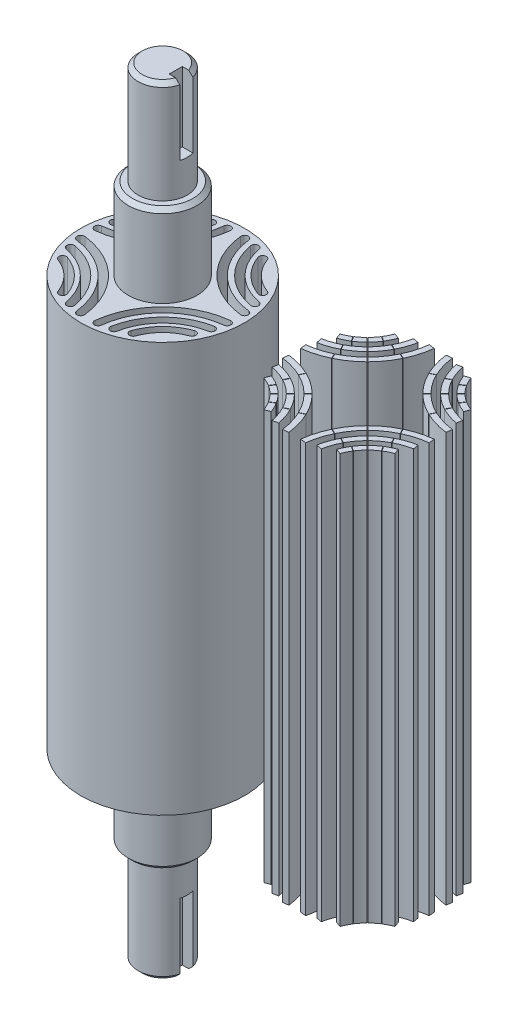
SolidWorks part; units mm, degrees
ref_plane "前视基准面" through (0, 0, 0) normal (0, 0, 1) x (1, 0, 0)
ref_plane "上视基准面" through (0, 0, 0) normal (0, 1, 0) x (1, 0, 0)
ref_plane "右视基准面" through (0, 0, 0) normal (1, 0, 0) x (0, 0, -1)
sketch "草图1" plane through (0, 0, 0) normal (0, 1, 0) x (1, 0, 0)
  circle A0 centre (0, 0) radius 20
extrude "凸台-拉伸1" add sketch "草图1" along normal blind 50
sketch "草图3" plane through (0, 50, 0) normal (0, 1, 0) x (1, 0, 0)
  circle A0 centre (0, 0) radius 8.4
extrude "凸台-拉伸2" add sketch "草图3" along normal blind 20
sketch "草图4" plane through (0, 70, 0) normal (0, 1, 0) x (1, 0, 0)
  circle A0 centre (0, 0) radius 6
extrude "凸台-拉伸3" add sketch "草图4" along normal blind 25
chamfer "倒角1" distance 1 angle 45 1 edges at (0, 70, 8.4)
chamfer "倒角2" distance 1 angle 45 1 edges at (0, 95, 6)
ref_plane "基准面1" through (10, 0, 0) normal (1, 0, 0) x (0, 0, -1)
sketch "草图5" plane through (10, 0, 0) normal (1, 0, 0) x (0, 0, -1)
  line L0 (-6, 94) -> (6, 94) construction
  line L1 (-1.6, 110) -> (1.6, 110)
  line L2 (-1.6, 110) -> (-1.6, 78)
  line L3 (-1.6, 78) -> (1.6, 78)
  line L4 (1.6, 110) -> (1.6, 78)
  line L5 (-1.6, 110) -> (1.6, 78) construction
  line L6 (-1.6, 78) -> (1.6, 110) construction
  point P0 (0, 94)
  dimension "D1" = 3.2
  dimension "D2" = 32
extrude "切除-拉伸1" cut sketch "草图5" against normal blind 6.8
sketch "草图6" plane through (0, 0, 0) normal (0, -1, 0) x (1, 0, 0)
  line L0 (0, 0) -> (0, 20) construction
  line L1 (0, 0) -> (20, 0) construction
  line L2 (0, 0) -> (19.8955, 19.8955) construction
  circle A0 centre (0, 0) radius 8.4 construction
  circle A1 centre (0, 0) radius 20 construction
  circle A2 centre (0, 0) radius 18 construction
  circle A3 centre (19.8955, 19.8955) radius 17.8842 construction
  circle A4 centre (19.8955, 19.8955) radius 15 construction
  circle A5 centre (19.8955, 19.8955) radius 12 construction
  arc A6 (2.126, 17.874) -> (17.874, 2.126) centre (19.8955, 19.8955) ccw construction
  arc A7 (1.2318, 17.7723) -> (17.7723, 1.2318) centre (19.8955, 19.8955) ccw
  arc A8 (3.0202, 17.9757) -> (17.9757, 3.0202) centre (19.8955, 19.8955) ccw
  arc A9 (3.0202, 17.9757) -> (1.2318, 17.7723) centre (2.126, 17.874) ccw
  arc A10 (17.7723, 1.2318) -> (17.9757, 3.0202) centre (17.874, 2.126) ccw
  arc A11 (5.3183, 17.1964) -> (17.1964, 5.3183) centre (19.8955, 19.8955) ccw construction
  arc A12 (4.4334, 17.0325) -> (17.0325, 4.4334) centre (19.8955, 19.8955) ccw
  arc A13 (6.2033, 17.3602) -> (17.3602, 6.2033) centre (19.8955, 19.8955) ccw
  arc A14 (6.2033, 17.3602) -> (4.4334, 17.0325) centre (5.3183, 17.1964) ccw
  arc A15 (17.0325, 4.4334) -> (17.3602, 6.2033) centre (17.1964, 5.3183) ccw
  arc A16 (8.6143, 15.8049) -> (15.8049, 8.6143) centre (19.8955, 19.8955) ccw construction
  arc A17 (7.7682, 15.4981) -> (15.4981, 7.7682) centre (19.8955, 19.8955) ccw
  arc A18 (9.4604, 16.1117) -> (16.1117, 9.4604) centre (19.8955, 19.8955) ccw
  arc A19 (9.4604, 16.1117) -> (7.7682, 15.4981) centre (8.6143, 15.8049) ccw
  arc A20 (15.4981, 7.7682) -> (16.1117, 9.4604) centre (15.8049, 8.6143) ccw
  arc A21 (17.874, -2.126) -> (2.126, -17.874) centre (19.8955, -19.8955) ccw construction
  arc A22 (17.7723, -1.2318) -> (1.2318, -17.7723) centre (19.8955, -19.8955) ccw
  arc A23 (17.9757, -3.0202) -> (3.0202, -17.9757) centre (19.8955, -19.8955) ccw
  arc A24 (17.9757, -3.0202) -> (17.7723, -1.2318) centre (17.874, -2.126) ccw
  arc A25 (1.2318, -17.7723) -> (3.0202, -17.9757) centre (2.126, -17.874) ccw
  arc A26 (17.1964, -5.3183) -> (5.3183, -17.1964) centre (19.8955, -19.8955) ccw construction
  arc A27 (17.0325, -4.4334) -> (4.4334, -17.0325) centre (19.8955, -19.8955) ccw
  arc A28 (17.3602, -6.2033) -> (6.2033, -17.3602) centre (19.8955, -19.8955) ccw
  arc A29 (17.3602, -6.2033) -> (17.0325, -4.4334) centre (17.1964, -5.3183) ccw
  arc A30 (4.4334, -17.0325) -> (6.2033, -17.3602) centre (5.3183, -17.1964) ccw
  arc A31 (15.8049, -8.6143) -> (8.6143, -15.8049) centre (19.8955, -19.8955) ccw construction
  arc A32 (15.4981, -7.7682) -> (7.7682, -15.4981) centre (19.8955, -19.8955) ccw
  arc A33 (16.1117, -9.4604) -> (9.4604, -16.1117) centre (19.8955, -19.8955) ccw
  arc A34 (16.1117, -9.4604) -> (15.4981, -7.7682) centre (15.8049, -8.6143) ccw
  arc A35 (7.7682, -15.4981) -> (9.4604, -16.1117) centre (8.6143, -15.8049) ccw
  arc A36 (-2.126, -17.874) -> (-17.874, -2.126) centre (-19.8955, -19.8955) ccw construction
  arc A37 (-1.2318, -17.7723) -> (-17.7723, -1.2318) centre (-19.8955, -19.8955) ccw
  arc A38 (-3.0202, -17.9757) -> (-17.9757, -3.0202) centre (-19.8955, -19.8955) ccw
  arc A39 (-3.0202, -17.9757) -> (-1.2318, -17.7723) centre (-2.126, -17.874) ccw
  arc A40 (-17.7723, -1.2318) -> (-17.9757, -3.0202) centre (-17.874, -2.126) ccw
  arc A41 (-5.3183, -17.1964) -> (-17.1964, -5.3183) centre (-19.8955, -19.8955) ccw construction
  arc A42 (-4.4334, -17.0325) -> (-17.0325, -4.4334) centre (-19.8955, -19.8955) ccw
  arc A43 (-6.2033, -17.3602) -> (-17.3602, -6.2033) centre (-19.8955, -19.8955) ccw
  arc A44 (-6.2033, -17.3602) -> (-4.4334, -17.0325) centre (-5.3183, -17.1964) ccw
  arc A45 (-17.0325, -4.4334) -> (-17.3602, -6.2033) centre (-17.1964, -5.3183) ccw
  arc A46 (-8.6143, -15.8049) -> (-15.8049, -8.6143) centre (-19.8955, -19.8955) ccw construction
  arc A47 (-7.7682, -15.4981) -> (-15.4981, -7.7682) centre (-19.8955, -19.8955) ccw
  arc A48 (-9.4604, -16.1117) -> (-16.1117, -9.4604) centre (-19.8955, -19.8955) ccw
  arc A49 (-9.4604, -16.1117) -> (-7.7682, -15.4981) centre (-8.6143, -15.8049) ccw
  arc A50 (-15.4981, -7.7682) -> (-16.1117, -9.4604) centre (-15.8049, -8.6143) ccw
  arc A51 (-17.874, 2.126) -> (-2.126, 17.874) centre (-19.8955, 19.8955) ccw construction
  arc A52 (-17.7723, 1.2318) -> (-1.2318, 17.7723) centre (-19.8955, 19.8955) ccw
  arc A53 (-17.9757, 3.0202) -> (-3.0202, 17.9757) centre (-19.8955, 19.8955) ccw
  arc A54 (-17.9757, 3.0202) -> (-17.7723, 1.2318) centre (-17.874, 2.126) ccw
  arc A55 (-1.2318, 17.7723) -> (-3.0202, 17.9757) centre (-2.126, 17.874) ccw
  arc A56 (-17.1964, 5.3183) -> (-5.3183, 17.1964) centre (-19.8955, 19.8955) ccw construction
  arc A57 (-17.0325, 4.4334) -> (-4.4334, 17.0325) centre (-19.8955, 19.8955) ccw
  arc A58 (-17.3602, 6.2033) -> (-6.2033, 17.3602) centre (-19.8955, 19.8955) ccw
  arc A59 (-17.3602, 6.2033) -> (-17.0325, 4.4334) centre (-17.1964, 5.3183) ccw
  arc A60 (-4.4334, 17.0325) -> (-6.2033, 17.3602) centre (-5.3183, 17.1964) ccw
  arc A61 (-15.8049, 8.6143) -> (-8.6143, 15.8049) centre (-19.8955, 19.8955) ccw construction
  arc A62 (-15.4981, 7.7682) -> (-7.7682, 15.4981) centre (-19.8955, 19.8955) ccw
  arc A63 (-16.1117, 9.4604) -> (-9.4604, 16.1117) centre (-19.8955, 19.8955) ccw
  arc A64 (-16.1117, 9.4604) -> (-15.4981, 7.7682) centre (-15.8049, 8.6143) ccw
  arc A65 (-7.7682, 15.4981) -> (-9.4604, 16.1117) centre (-8.6143, 15.8049) ccw
  point P15 (7.2495, 7.2495)
  point P23 (9.4127, 9.4127)
  point P31 (11.4103, 11.4103)
  point P42 (7.2495, -7.2495)
  point P50 (9.4127, -9.4127)
  point P58 (11.4103, -11.4103)
  point P66 (-7.2495, -7.2495)
  point P74 (-9.4127, -9.4127)
  point P82 (-11.4103, -11.4103)
  point P90 (-7.2495, 7.2495)
  point P98 (-9.4127, 9.4127)
  point P106 (-11.4103, 11.4103)
  point P111 (0, 0)
  dimension "D1" = 4
extrude "切除-拉伸2" cut sketch "草图6" against normal up to next
mirror "镜向1" about plane through (0, 0, 0) normal (0, 1, 0) of bodies 110
ref_plane "基准面2" through (0, 100, 0) normal (0, 1, 0) x (1, 0, 0)
sketch "草图7" plane through (0, 100, 0) normal (0, 1, 0) x (1, 0, 0)
  line L0 (19.8955, 19.8955) -> (0, 0) construction
  line L1 (19.8955, 19.8955) -> (7.7682, 15.4981) construction
  line L2 (19.8955, 19.8955) -> (4.4334, 17.0325) construction
  line L3 (19.8955, 19.8955) -> (1.2318, 17.7723) construction
  line L4 (19.8955, 19.8955) -> (1.4795, 8.1632) construction
  line L5 (19.8955, 19.8955) -> (1.4863, 10.2099) construction
  line L6 (19.8955, 19.8955) -> (1.6731, 11.1061) construction
  line L16 (10.3383, 13.8662) -> (9.1576, 13.114)
  line L17 (10.3921, 13.7819) -> (9.2113, 13.0297)
  line L18 (9.2876, 16.0017) -> (7.9734, 15.5193)
  line L19 (11.8699, 11.9406) -> (10.8799, 10.9506)
  line L20 (9.8723, 9.943) -> (8.8824, 8.9531)
  line L21 (6.015, 17.2791) -> (4.6392, 17.0198)
  line L22 (7.3718, 13.363) -> (6.1328, 12.7111)
  line L23 (7.4184, 13.2745) -> (6.1794, 12.6226)
  line L24 (7.7091, 7.7799) -> (6.7192, 6.7899)
  line L25 (4.3961, 12.475) -> (3.1351, 11.8668)
  line L26 (4.4395, 12.3849) -> (3.1785, 11.7767)
  line L27 (2.8268, 17.9072) -> (1.4362, 17.7452)
  arc A0 (17.0325, 4.4334) -> (17.3602, 6.2033) centre (17.1964, 5.3183) ccw construction
  arc A1 (17.7723, 1.2318) -> (17.9757, 3.0202) centre (17.874, 2.126) ccw construction
  arc A2 (3.0202, 17.9757) -> (1.2318, 17.7723) centre (2.126, 17.874) ccw construction
  arc A3 (6.2033, 17.3602) -> (4.4334, 17.0325) centre (5.3183, 17.1964) ccw construction
  arc A4 (15.4981, 7.7682) -> (16.1117, 9.4604) centre (15.8049, 8.6143) ccw construction
  arc A5 (9.4604, 16.1117) -> (7.7682, 15.4981) centre (8.6143, 15.8049) ccw construction
  arc A6 (9.4604, 16.1117) -> (16.1117, 9.4604) centre (19.8955, 19.8955) ccw construction
  arc A7 (7.7682, 15.4981) -> (15.4981, 7.7682) centre (19.8955, 19.8955) ccw construction
  arc A8 (6.2033, 17.3602) -> (17.3602, 6.2033) centre (19.8955, 19.8955) ccw construction
  arc A9 (4.4334, 17.0325) -> (17.0325, 4.4334) centre (19.8955, 19.8955) ccw construction
  arc A10 (1.2318, 17.7723) -> (17.7723, 1.2318) centre (19.8955, 19.8955) ccw construction
  arc A11 (3.0202, 17.9757) -> (17.9757, 3.0202) centre (19.8955, 19.8955) ccw construction
  arc A12 (17.0325, 4.4334) -> (17.3602, 6.2033) centre (17.1964, 5.3183) ccw construction
  arc A13 (17.7723, 1.2318) -> (17.9757, 3.0202) centre (17.874, 2.126) ccw construction
  arc A14 (3.0202, 17.9757) -> (1.2318, 17.7723) centre (2.126, 17.874) ccw construction
  arc A15 (6.2033, 17.3602) -> (4.4334, 17.0325) centre (5.3183, 17.1964) ccw construction
  arc A16 (15.4981, 7.7682) -> (16.1117, 9.4604) centre (15.8049, 8.6143) ccw construction
  arc A17 (9.4604, 16.1117) -> (7.7682, 15.4981) centre (8.6143, 15.8049) ccw construction
  arc A18 (9.4604, 16.1117) -> (16.1117, 9.4604) centre (19.8955, 19.8955) ccw construction
  arc A19 (7.7682, 15.4981) -> (15.4981, 7.7682) centre (19.8955, 19.8955) ccw construction
  arc A20 (6.2033, 17.3602) -> (17.3602, 6.2033) centre (19.8955, 19.8955) ccw construction
  arc A21 (4.4334, 17.0325) -> (17.0325, 4.4334) centre (19.8955, 19.8955) ccw construction
  arc A22 (1.2318, 17.7723) -> (17.7723, 1.2318) centre (19.8955, 19.8955) ccw construction
  arc A23 (3.0202, 17.9757) -> (17.9757, 3.0202) centre (19.8955, 19.8955) ccw construction
  arc A24 (6.015, 17.2791) -> (7.3667, 13.3731) centre (19.8955, 19.8955) ccw
  arc A25 (7.4184, 13.2745) -> (9.8691, 9.9463) centre (19.8955, 19.8955) ccw
  arc A26 (10.3921, 13.7819) -> (11.868, 11.9425) centre (19.8955, 19.8955) ccw
  arc A27 (4.6392, 17.0198) -> (6.1329, 12.7112) centre (19.8955, 19.8955) ccw
  arc A28 (6.1794, 12.6226) -> (8.9177, 8.9177) centre (19.8955, 19.8955) ccw
  arc A29 (2.8268, 17.9072) -> (4.3963, 12.4747) centre (19.8955, 19.8955) ccw
  arc A30 (9.2113, 13.0297) -> (10.8747, 10.9559) centre (19.8955, 19.8955) ccw
  arc A31 (1.4362, 17.7452) -> (3.1352, 11.8668) centre (19.8955, 19.8955) ccw
  arc A32 (9.2876, 16.0017) -> (10.3393, 13.8649) centre (19.8955, 19.8955) ccw
  arc A33 (7.9734, 15.5193) -> (9.1527, 13.1219) centre (19.8955, 19.8955) ccw
  arc A34 (4.4395, 12.3849) -> (7.7011, 7.7879) centre (19.8955, 19.8955) ccw
  arc A35 (3.1785, 11.7767) -> (6.7041, 6.8051) centre (19.8955, 19.8955) ccw
  point P69 (11.9052, 11.9052)
  point P70 (11.8699, 11.9406)
  point P71 (10.8799, 10.9506)
  point P72 (10.9153, 10.9153)
  dimension "D2" = 25.069
  dimension "D3" = 34.51
  dimension "D4" = 38.51
  dimension "D5" = 12.5
  dimension "D6" = 17.25
  dimension "D7" = 19.25
ref_plane "基准面3" through (0, 50, 0) normal (0, 1, 0) x (1, 0, 0)
sketch "草图8" plane through (0, 50, 0) normal (0, 1, 0) x (1, 0, 0)
  line L0 (11.8699, 11.9406) -> (10.8799, 10.9506) construction
  line L1 (10.3921, 13.7819) -> (9.2113, 13.0297) construction
  line L2 (10.3383, 13.8662) -> (9.1576, 13.114) construction
  line L3 (9.2876, 16.0017) -> (7.9734, 15.5193) construction
  line L4 (6.015, 17.2791) -> (4.6392, 17.0198) construction
  line L5 (7.3718, 13.363) -> (6.1328, 12.7111) construction
  line L6 (7.4184, 13.2745) -> (6.1794, 12.6226) construction
  line L7 (9.8723, 9.943) -> (8.8824, 8.9531) construction
  line L8 (7.7091, 7.7799) -> (6.7192, 6.7899) construction
  line L9 (4.4395, 12.3849) -> (3.1785, 11.7767) construction
  line L10 (4.3961, 12.475) -> (3.1351, 11.8668) construction
  line L11 (2.8268, 17.9072) -> (1.4362, 17.7452) construction
  line L12 (11.8699, 11.9406) -> (10.8799, 10.9506)
  line L13 (10.3921, 13.7819) -> (9.2113, 13.0297)
  line L14 (10.3384, 13.8663) -> (9.1576, 13.114)
  line L15 (9.2876, 16.0017) -> (7.9734, 15.5193)
  line L16 (6.015, 17.2791) -> (4.6392, 17.0198)
  line L17 (7.3718, 13.363) -> (6.1328, 12.7111)
  line L18 (7.4184, 13.2745) -> (6.1794, 12.6226)
  line L19 (9.8723, 9.943) -> (8.8824, 8.9531)
  line L20 (7.7091, 7.7799) -> (6.7192, 6.7899)
  line L21 (4.4395, 12.3849) -> (3.1785, 11.7767)
  line L22 (4.3961, 12.475) -> (3.1351, 11.8668)
  line L23 (2.8268, 17.9072) -> (1.4362, 17.7452)
  line L24 (11.9406, -11.8699) -> (10.9506, -10.8799)
  line L25 (0, 0) -> (16.5885, 16.5885) construction
  line L26 (17.9072, 2.8268) -> (17.7452, 1.4362)
  line L27 (12.475, 4.3961) -> (11.8668, 3.1351)
  line L28 (12.3849, 4.4395) -> (11.7767, 3.1785)
  line L29 (7.7799, 7.7091) -> (6.7899, 6.7192)
  line L30 (9.943, 9.8723) -> (8.9531, 8.8824)
  line L31 (13.2745, 7.4184) -> (12.6226, 6.1794)
  line L32 (13.363, 7.3718) -> (12.7111, 6.1328)
  line L33 (17.2791, 6.015) -> (17.0198, 4.6392)
  line L34 (16.0017, 9.2876) -> (15.5193, 7.9734)
  line L35 (13.8663, 10.3384) -> (13.114, 9.1576)
  line L36 (13.7819, 10.3921) -> (13.0297, 9.2113)
  line L37 (11.9406, 11.8699) -> (10.9506, 10.8799)
  line L38 (13.7819, -10.3921) -> (13.0297, -9.2113)
  line L39 (13.8663, -10.3384) -> (13.114, -9.1576)
  line L40 (16.0017, -9.2876) -> (15.5193, -7.9734)
  line L41 (17.2791, -6.015) -> (17.0198, -4.6392)
  line L42 (13.363, -7.3718) -> (12.7111, -6.1328)
  line L43 (13.2745, -7.4184) -> (12.6226, -6.1794)
  line L44 (9.943, -9.8723) -> (8.9531, -8.8824)
  line L45 (7.7799, -7.7091) -> (6.7899, -6.7192)
  line L46 (12.3849, -4.4395) -> (11.7767, -3.1785)
  line L47 (12.475, -4.3961) -> (11.8668, -3.1351)
  line L48 (17.9072, -2.8268) -> (17.7452, -1.4362)
  line L49 (2.8268, -17.9072) -> (1.4362, -17.7452)
  line L50 (4.3961, -12.475) -> (3.1351, -11.8668)
  line L51 (4.4395, -12.3849) -> (3.1785, -11.7767)
  line L52 (7.7091, -7.7799) -> (6.7192, -6.7899)
  line L53 (9.8723, -9.943) -> (8.8824, -8.9531)
  line L54 (7.4184, -13.2745) -> (6.1794, -12.6226)
  line L55 (7.3718, -13.363) -> (6.1328, -12.7111)
  line L56 (6.015, -17.2791) -> (4.6392, -17.0198)
  line L57 (9.2876, -16.0017) -> (7.9734, -15.5193)
  line L58 (10.3384, -13.8663) -> (9.1576, -13.114)
  line L59 (10.3921, -13.7819) -> (9.2113, -13.0297)
  line L60 (11.8699, -11.9406) -> (10.8799, -10.9506)
  line L61 (-11.8699, -11.9406) -> (-10.8799, -10.9506)
  line L62 (-10.3921, -13.7819) -> (-9.2113, -13.0297)
  line L63 (-10.3384, -13.8663) -> (-9.1576, -13.114)
  line L64 (-9.2876, -16.0017) -> (-7.9734, -15.5193)
  line L65 (-6.015, -17.2791) -> (-4.6392, -17.0198)
  line L66 (-7.3718, -13.363) -> (-6.1328, -12.7111)
  line L67 (-7.4184, -13.2745) -> (-6.1794, -12.6226)
  line L68 (-9.8723, -9.943) -> (-8.8824, -8.9531)
  line L69 (-7.7091, -7.7799) -> (-6.7192, -6.7899)
  line L70 (-4.4395, -12.3849) -> (-3.1785, -11.7767)
  line L71 (-4.3961, -12.475) -> (-3.1351, -11.8668)
  line L72 (-2.8268, -17.9072) -> (-1.4362, -17.7452)
  line L73 (-17.9072, -2.8268) -> (-17.7452, -1.4362)
  line L74 (-12.475, -4.3961) -> (-11.8668, -3.1351)
  line L75 (-12.3849, -4.4395) -> (-11.7767, -3.1785)
  line L76 (-7.7799, -7.7091) -> (-6.7899, -6.7192)
  line L77 (-9.943, -9.8723) -> (-8.9531, -8.8824)
  line L78 (-13.2745, -7.4184) -> (-12.6226, -6.1794)
  line L79 (-13.363, -7.3718) -> (-12.7111, -6.1328)
  line L80 (-17.2791, -6.015) -> (-17.0198, -4.6392)
  line L81 (-16.0017, -9.2876) -> (-15.5193, -7.9734)
  line L82 (-13.8663, -10.3384) -> (-13.114, -9.1576)
  line L83 (-13.7819, -10.3921) -> (-13.0297, -9.2113)
  line L84 (-11.9406, -11.8699) -> (-10.9506, -10.8799)
  line L85 (-11.9406, 11.8699) -> (-10.9506, 10.8799)
  line L86 (-13.7819, 10.3921) -> (-13.0297, 9.2113)
  line L87 (-13.8663, 10.3384) -> (-13.114, 9.1576)
  line L88 (-16.0017, 9.2876) -> (-15.5193, 7.9734)
  line L89 (-17.2791, 6.015) -> (-17.0198, 4.6392)
  line L90 (-13.363, 7.3718) -> (-12.7111, 6.1328)
  line L91 (-13.2745, 7.4184) -> (-12.6226, 6.1794)
  line L92 (-9.943, 9.8723) -> (-8.9531, 8.8824)
  line L93 (-7.7799, 7.7091) -> (-6.7899, 6.7192)
  line L94 (-12.3849, 4.4395) -> (-11.7767, 3.1785)
  line L95 (-12.475, 4.3961) -> (-11.8668, 3.1351)
  line L96 (-17.9072, 2.8268) -> (-17.7452, 1.4362)
  line L97 (-2.8268, 17.9072) -> (-1.4362, 17.7452)
  line L98 (-4.3961, 12.475) -> (-3.1351, 11.8668)
  line L99 (-4.4395, 12.3849) -> (-3.1785, 11.7767)
  line L100 (-7.7091, 7.7799) -> (-6.7192, 6.7899)
  line L101 (-9.8723, 9.943) -> (-8.8824, 8.9531)
  line L102 (-7.4184, 13.2745) -> (-6.1794, 12.6226)
  line L103 (-7.3718, 13.363) -> (-6.1328, 12.7111)
  line L104 (-6.015, 17.2791) -> (-4.6392, 17.0198)
  line L105 (-9.2876, 16.0017) -> (-7.9734, 15.5193)
  line L106 (-10.3384, 13.8663) -> (-9.1576, 13.114)
  line L107 (-10.3921, 13.7819) -> (-9.2113, 13.0297)
  line L108 (-11.8699, 11.9406) -> (-10.8799, 10.9506)
  arc A0 (13.7819, 10.3921) -> (11.9406, 11.8699) centre (19.6081, 19.5374) cw
  arc A1 (13.0297, 9.2113) -> (10.9506, 10.8799) centre (19.6081, 19.5374) cw
  arc A2 (15.5193, 7.9734) -> (13.114, 9.1576) centre (19.8971, 19.8997) cw
  arc A3 (16.0017, 9.2876) -> (13.8663, 10.3384) centre (19.8959, 19.8964) cw
  arc A4 (12.6226, 6.1794) -> (8.9531, 8.8824) centre (19.6978, 19.6271) cw
  arc A5 (13.2745, 7.4184) -> (9.943, 9.8723) centre (19.6978, 19.6271) cw
  arc A6 (17.0198, 4.6392) -> (12.7111, 6.1328) centre (19.8959, 19.8974) cw
  arc A7 (17.2791, 6.015) -> (13.363, 7.3718) centre (19.8959, 19.8976) cw
  arc A8 (11.7767, 3.1785) -> (6.7899, 6.7192) centre (19.7224, 19.6517) cw
  arc A9 (12.3849, 4.4395) -> (7.7799, 7.7091) centre (19.7224, 19.6517) cw
  arc A10 (17.7452, 1.4362) -> (11.8668, 3.1351) centre (19.8957, 19.8968) cw
  arc A11 (17.9072, 2.8268) -> (12.475, 4.3961) centre (19.8957, 19.8969) cw
  arc A12 (10.3921, -13.7819) -> (11.8699, -11.9406) centre (19.5374, -19.6081) cw
  arc A13 (9.2113, -13.0297) -> (10.8799, -10.9506) centre (19.5374, -19.6081) cw
  arc A14 (7.9734, -15.5193) -> (9.1576, -13.114) centre (19.8997, -19.8971) cw
  arc A15 (9.2876, -16.0017) -> (10.3384, -13.8663) centre (19.8964, -19.8959) cw
  arc A16 (6.1794, -12.6226) -> (8.8824, -8.9531) centre (19.6271, -19.6978) cw
  arc A17 (7.4184, -13.2745) -> (9.8723, -9.943) centre (19.6271, -19.6978) cw
  arc A18 (4.6392, -17.0198) -> (6.1328, -12.7111) centre (19.8974, -19.8959) cw
  arc A19 (6.015, -17.2791) -> (7.3718, -13.363) centre (19.8976, -19.8959) cw
  arc A20 (3.1785, -11.7767) -> (6.7192, -6.7899) centre (19.6517, -19.7224) cw
  arc A21 (4.4395, -12.3849) -> (7.7091, -7.7799) centre (19.6517, -19.7224) cw
  arc A22 (2.8268, 17.9072) -> (4.3961, 12.475) centre (19.8969, 19.8957) ccw
  arc A23 (1.4362, 17.7452) -> (3.1351, 11.8668) centre (19.8968, 19.8957) ccw
  arc A24 (4.4395, 12.3849) -> (7.7091, 7.7799) centre (19.6517, 19.7224) ccw
  arc A25 (3.1785, 11.7767) -> (6.7192, 6.7899) centre (19.6517, 19.7224) ccw
  arc A26 (6.015, 17.2791) -> (7.3718, 13.363) centre (19.8976, 19.8959) ccw
  arc A27 (4.6392, 17.0198) -> (6.1328, 12.7111) centre (19.8974, 19.8959) ccw
  arc A28 (7.4184, 13.2745) -> (9.8723, 9.943) centre (19.6271, 19.6978) ccw
  arc A29 (6.1794, 12.6226) -> (8.8824, 8.9531) centre (19.6271, 19.6978) ccw
  arc A30 (9.2876, 16.0017) -> (10.3384, 13.8663) centre (19.8964, 19.8959) ccw
  arc A31 (7.9734, 15.5193) -> (9.1576, 13.114) centre (19.8997, 19.8971) ccw
  arc A32 (9.2113, 13.0297) -> (10.8799, 10.9506) centre (19.5374, 19.6081) ccw
  arc A33 (10.3921, 13.7819) -> (11.8699, 11.9406) centre (19.5374, 19.6081) ccw
  arc A34 (1.4362, -17.7452) -> (3.1351, -11.8668) centre (19.8968, -19.8957) cw
  arc A35 (2.8268, -17.9072) -> (4.3961, -12.475) centre (19.8969, -19.8957) cw
  arc A36 (17.9072, -2.8268) -> (12.475, -4.3961) centre (19.8957, -19.8969) ccw
  arc A37 (17.7452, -1.4362) -> (11.8668, -3.1351) centre (19.8957, -19.8968) ccw
  arc A38 (12.3849, -4.4395) -> (7.7799, -7.7091) centre (19.7224, -19.6517) ccw
  arc A39 (11.7767, -3.1785) -> (6.7899, -6.7192) centre (19.7224, -19.6517) ccw
  arc A40 (17.2791, -6.015) -> (13.363, -7.3718) centre (19.8959, -19.8976) ccw
  arc A41 (17.0198, -4.6392) -> (12.7111, -6.1328) centre (19.8959, -19.8974) ccw
  arc A42 (13.2745, -7.4184) -> (9.943, -9.8723) centre (19.6978, -19.6271) ccw
  arc A43 (12.6226, -6.1794) -> (8.9531, -8.8824) centre (19.6978, -19.6271) ccw
  arc A44 (16.0017, -9.2876) -> (13.8663, -10.3384) centre (19.8959, -19.8964) ccw
  arc A45 (15.5193, -7.9734) -> (13.114, -9.1576) centre (19.8971, -19.8997) ccw
  arc A46 (13.0297, -9.2113) -> (10.9506, -10.8799) centre (19.6081, -19.5374) ccw
  arc A47 (13.7819, -10.3921) -> (11.9406, -11.8699) centre (19.6081, -19.5374) ccw
  arc A48 (-13.7819, -10.3921) -> (-11.9406, -11.8699) centre (-19.6081, -19.5374) cw
  arc A49 (-13.0297, -9.2113) -> (-10.9506, -10.8799) centre (-19.6081, -19.5374) cw
  arc A50 (-15.5193, -7.9734) -> (-13.114, -9.1576) centre (-19.8971, -19.8997) cw
  arc A51 (-16.0017, -9.2876) -> (-13.8663, -10.3384) centre (-19.8959, -19.8964) cw
  arc A52 (-12.6226, -6.1794) -> (-8.9531, -8.8824) centre (-19.6978, -19.6271) cw
  arc A53 (-13.2745, -7.4184) -> (-9.943, -9.8723) centre (-19.6978, -19.6271) cw
  arc A54 (-17.0198, -4.6392) -> (-12.7111, -6.1328) centre (-19.8959, -19.8974) cw
  arc A55 (-17.2791, -6.015) -> (-13.363, -7.3718) centre (-19.8959, -19.8976) cw
  arc A56 (-11.7767, -3.1785) -> (-6.7899, -6.7192) centre (-19.7224, -19.6517) cw
  arc A57 (-12.3849, -4.4395) -> (-7.7799, -7.7091) centre (-19.7224, -19.6517) cw
  arc A58 (-17.7452, -1.4362) -> (-11.8668, -3.1351) centre (-19.8957, -19.8968) cw
  arc A59 (-17.9072, -2.8268) -> (-12.475, -4.3961) centre (-19.8957, -19.8969) cw
  arc A60 (-2.8268, -17.9072) -> (-4.3961, -12.475) centre (-19.8969, -19.8957) ccw
  arc A61 (-1.4362, -17.7452) -> (-3.1351, -11.8668) centre (-19.8968, -19.8957) ccw
  arc A62 (-4.4395, -12.3849) -> (-7.7091, -7.7799) centre (-19.6517, -19.7224) ccw
  arc A63 (-3.1785, -11.7767) -> (-6.7192, -6.7899) centre (-19.6517, -19.7224) ccw
  arc A64 (-6.015, -17.2791) -> (-7.3718, -13.363) centre (-19.8976, -19.8959) ccw
  arc A65 (-4.6392, -17.0198) -> (-6.1328, -12.7111) centre (-19.8974, -19.8959) ccw
  arc A66 (-7.4184, -13.2745) -> (-9.8723, -9.943) centre (-19.6271, -19.6978) ccw
  arc A67 (-6.1794, -12.6226) -> (-8.8824, -8.9531) centre (-19.6271, -19.6978) ccw
  arc A68 (-9.2876, -16.0017) -> (-10.3384, -13.8663) centre (-19.8964, -19.8959) ccw
  arc A69 (-7.9734, -15.5193) -> (-9.1576, -13.114) centre (-19.8997, -19.8971) ccw
  arc A70 (-9.2113, -13.0297) -> (-10.8799, -10.9506) centre (-19.5374, -19.6081) ccw
  arc A71 (-10.3921, -13.7819) -> (-11.8699, -11.9406) centre (-19.5374, -19.6081) ccw
  arc A72 (-10.3921, 13.7819) -> (-11.8699, 11.9406) centre (-19.5374, 19.6081) cw
  arc A73 (-9.2113, 13.0297) -> (-10.8799, 10.9506) centre (-19.5374, 19.6081) cw
  arc A74 (-7.9734, 15.5193) -> (-9.1576, 13.114) centre (-19.8997, 19.8971) cw
  arc A75 (-9.2876, 16.0017) -> (-10.3384, 13.8663) centre (-19.8964, 19.8959) cw
  arc A76 (-6.1794, 12.6226) -> (-8.8824, 8.9531) centre (-19.6271, 19.6978) cw
  arc A77 (-7.4184, 13.2745) -> (-9.8723, 9.943) centre (-19.6271, 19.6978) cw
  arc A78 (-4.6392, 17.0198) -> (-6.1328, 12.7111) centre (-19.8974, 19.8959) cw
  arc A79 (-6.015, 17.2791) -> (-7.3718, 13.363) centre (-19.8976, 19.8959) cw
  arc A80 (-3.1785, 11.7767) -> (-6.7192, 6.7899) centre (-19.6517, 19.7224) cw
  arc A81 (-4.4395, 12.3849) -> (-7.7091, 7.7799) centre (-19.6517, 19.7224) cw
  arc A82 (-1.4362, 17.7452) -> (-3.1351, 11.8668) centre (-19.8968, 19.8957) cw
  arc A83 (-2.8268, 17.9072) -> (-4.3961, 12.475) centre (-19.8969, 19.8957) cw
  arc A84 (-17.9072, 2.8268) -> (-12.475, 4.3961) centre (-19.8957, 19.8969) ccw
  arc A85 (-17.7452, 1.4362) -> (-11.8668, 3.1351) centre (-19.8957, 19.8968) ccw
  arc A86 (-12.3849, 4.4395) -> (-7.7799, 7.7091) centre (-19.7224, 19.6517) ccw
  arc A87 (-11.7767, 3.1785) -> (-6.7899, 6.7192) centre (-19.7224, 19.6517) ccw
  arc A88 (-17.2791, 6.015) -> (-13.363, 7.3718) centre (-19.8959, 19.8976) ccw
  arc A89 (-17.0198, 4.6392) -> (-12.7111, 6.1328) centre (-19.8959, 19.8974) ccw
  arc A90 (-13.2745, 7.4184) -> (-9.943, 9.8723) centre (-19.6978, 19.6271) ccw
  arc A91 (-12.6226, 6.1794) -> (-8.9531, 8.8824) centre (-19.6978, 19.6271) ccw
  arc A92 (-16.0017, 9.2876) -> (-13.8663, 10.3384) centre (-19.8959, 19.8964) ccw
  arc A93 (-15.5193, 7.9734) -> (-13.114, 9.1576) centre (-19.8971, 19.8997) ccw
  arc A94 (-13.0297, 9.2113) -> (-10.9506, 10.8799) centre (-19.6081, 19.5374) ccw
  arc A95 (-13.7819, 10.3921) -> (-11.9406, 11.8699) centre (-19.6081, 19.5374) ccw
  point P283 (0, 0)
  dimension "D1" = 4
extrude "凸台-拉伸4" add sketch "草图8" against normal blind 100 separate body
move or copy body "实体-移动/复制1" bodies to move or copy 155 154 148 149 150 151 156 157 159 158 152 153 117 116 123 124 122 121 115 114 113 112 119 120 129 128 134 135 133 132 127 126 125 118 130 131 137 136 142 143 copy no translate (50, 0, 0)
